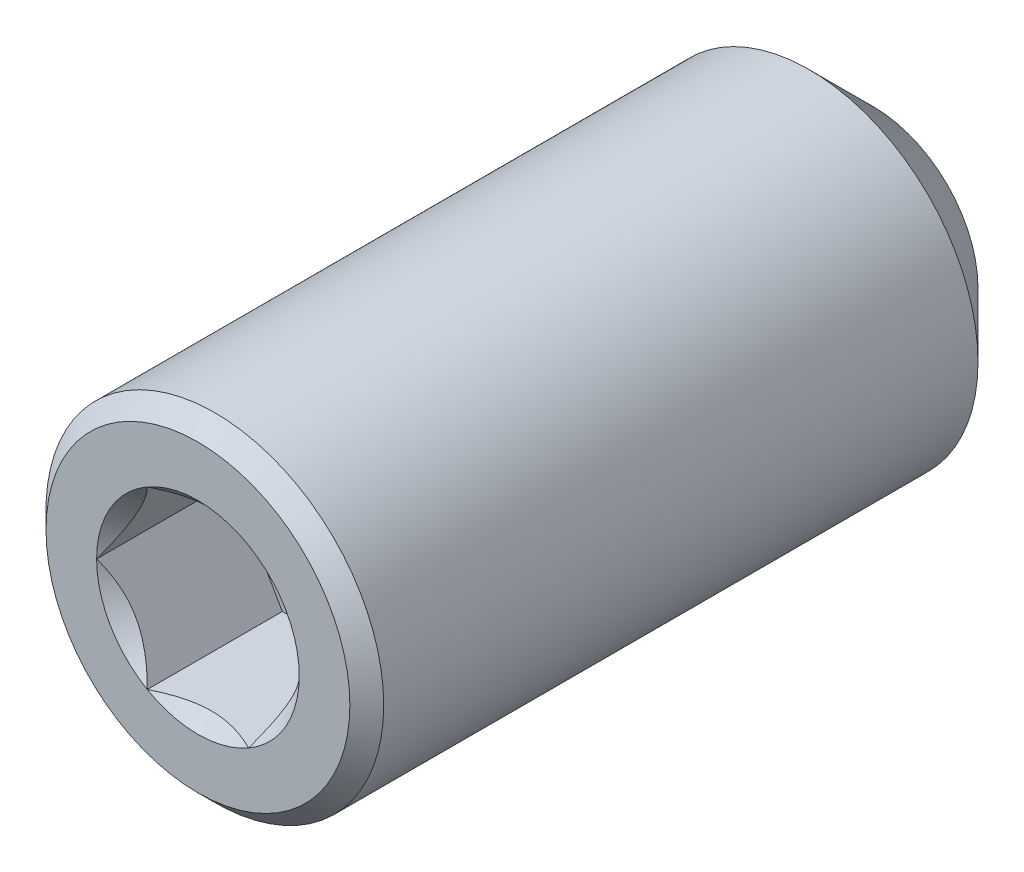
SolidWorks part; units mm, degrees
material "Galvanized Steel"
ref_plane "Front Plane" through (0, 0, 0) normal (0, 0, 1) x (1, 0, 0)
ref_plane "Top Plane" through (0, 0, 0) normal (0, 1, 0) x (1, 0, 0)
ref_plane "Right Plane" through (0, 0, 0) normal (1, 0, 0) x (0, 0, -1)
other "Configuration Table"
sketch "Sketch1" plane through (0, 0, 0) normal (0, 1, 0) x (1, 0, 0)
  line L0 (2.5, 5) -> (0, 5)
  line L1 (0, 5) -> (0, -5)
  line L2 (0, -5) -> (2.5, -5)
  line L3 (2.5, -5) -> (2.5, 5)
  line L4 (0, 5) -> (0, -5) construction
  line L5 (0, -5) -> (0, -10.6854) construction
  dimension "D1" = 5
  dimension "D2" = 10
revolve "Revolve1" add sketch "Sketch1" angle 360 about L4
sketch "Sketch2" plane through (0, 0, 5) normal (0, 0, 1) x (1, 0, 0)
  line L0 (-0.75, -1.299) -> (0.75, -1.299)
  line L1 (0.75, -1.299) -> (1.5, 0)
  line L2 (1.5, 0) -> (0.75, 1.299)
  line L3 (0.75, 1.299) -> (-0.75, 1.299)
  line L4 (-0.75, 1.299) -> (-1.5, 0)
  line L5 (-1.5, 0) -> (-0.75, -1.299)
extrude "Cut-Extrude1" cut sketch "Sketch2" against normal blind 2
chamfer "Chamfer1" distance 0.2505 angle 45 1 edges at (2.5, 0, 5)
chamfer "Chamfer2" distance 0.9505 angle 45 1 edges at (2.5, 0, -5)
cosmetic thread "Cosmetic Thread1" parameters "D2"=4.11
sketch "Sketch3" plane through (0, 0, 0) normal (0, 1, 0) x (1, 0, 0)
  line L2 (0, -3.5) -> (-1.5, -5)
  line L3 (-0.75, -5) -> (-1.5, -5) construction
  line L4 (-1.5, -3) -> (-1.5, -5) construction
  line L5 (-1.5, -5) -> (0, -5)
  line L6 (-2.2495, -5) -> (2.2495, -5) construction
  line L7 (0, -5) -> (0, -3.5)
  line L9 (0, -3.5) -> (0, 0) construction
  dimension "D1" = 45
revolve "Cut-Revolve1" cut sketch "Sketch3" angle 360 about L9
